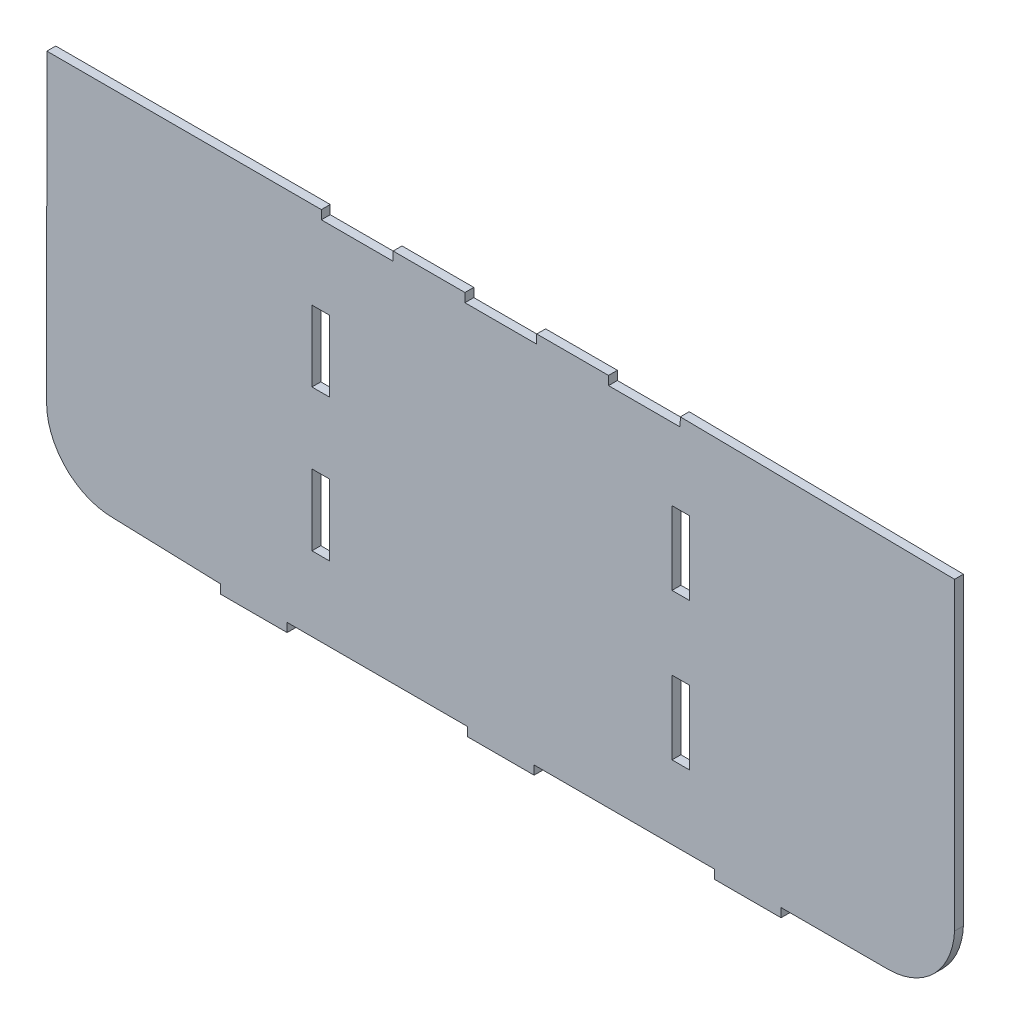
SolidWorks part; units mm, degrees
ref_plane "Front Plane" through (0, 0, 0) normal (0, 0, 1) x (1, 0, 0)
ref_plane "Top Plane" through (0, 0, 0) normal (0, 1, 0) x (1, 0, 0)
ref_plane "Right Plane" through (0, 0, 0) normal (1, 0, 0) x (0, 0, -1)
sketch "Sketch1" plane through (0, 0, 0) normal (0, 0, 1) x (1, 0, 0)
  line L12 (-444.5, 10.16) -> (-321.2, 6.2241)
  line L16 (-245, 6.2241) -> (-38.1, 6.2241)
  line L20 (38.1, 6.2241) -> (245, 6.2241)
  line L27 (205.7064, 435.61) -> (205.558, 425.45)
  line L28 (205.558, 425.45) -> (123.444, 425.45)
  line L29 (123.444, 425.45) -> (123.444, 435.61)
  line L30 (123.444, 435.61) -> (41.148, 435.61)
  line L31 (41.148, 435.61) -> (41.148, 425.45)
  line L32 (41.148, 425.45) -> (-41.148, 425.45)
  line L33 (-41.148, 425.45) -> (-41.148, 435.61)
  line L34 (-41.148, 435.61) -> (-123.444, 435.61)
  line L35 (-123.444, 435.61) -> (-123.444, 425.45)
  line L36 (-123.444, 425.45) -> (-205.74, 425.45)
  line L37 (-205.74, 425.45) -> (-205.74, 388.35)
  line L38 (-205.74, 388.35) -> (-230.3597, 388.35)
  line L39 (-520.3601, 435.61) -> (-520.7, 86.36)
  line L43 (-38.1, 6.2241) -> (-38.1, -3.9359) construction
  line L45 (38.1, 6.2241) -> (38.1, -3.9359) construction
  line L46 (38.1, 6.2241) -> (38.1, -3.9359)
  line L47 (-38.1, 6.2241) -> (-38.1, -3.9359)
  line L48 (245, 6.2241) -> (245, -3.9359) construction
  line L49 (321.2, 6.2241) -> (321.2, -3.9359) construction
  line L50 (245, 6.2241) -> (245, -3.9359)
  line L51 (321.2, 6.2241) -> (321.2, -3.9359)
  line L52 (-245, 6.2241) -> (-245, -3.9359) construction
  line L53 (-321.2, 6.2241) -> (-321.2, -3.9359) construction
  line L54 (-321.2, 6.2241) -> (-321.2, -3.9359)
  line L55 (-245, 6.2241) -> (-245, -3.9359)
  line L56 (216.5353, 174.4512) -> (216.5353, 90.3376) construction
  line L57 (216.5353, 342.6783) -> (216.5353, 258.5647) construction
  line L58 (216.5353, 174.4512) -> (216.5353, 90.3376)
  line L59 (216.5353, 342.6783) -> (216.5353, 258.5647)
  line L60 (-205.74, 425.45) -> (-205.74, 435.61)
  line L61 (-205.74, 435.61) -> (-520.3601, 435.61)
  line L62 (-216.5353, 172.7939) -> (-216.5353, 91.4769)
  line L63 (-216.5353, 335.4278) -> (-216.5353, 254.1108)
  line L64 (196.2153, 342.6783) -> (196.2153, 258.5647)
  line L65 (-196.2153, 335.4278) -> (-196.2153, 254.1108)
  line L66 (-196.2153, 172.7939) -> (-196.2153, 91.4769)
  line L67 (196.2153, 174.4512) -> (196.2153, 90.3376)
  line L68 (196.2153, 342.6783) -> (216.5353, 342.6783)
  line L69 (-196.2153, 335.4278) -> (-216.5353, 335.4278)
  line L70 (-216.5353, 254.1108) -> (-196.2153, 254.1108)
  line L71 (-196.2153, 172.7939) -> (-216.5353, 172.7939)
  line L72 (-196.2153, 91.4769) -> (-216.5353, 91.4769)
  line L73 (196.2153, 90.3376) -> (216.5353, 90.3376)
  line L74 (216.5353, 174.4512) -> (196.2153, 174.4512)
  line L75 (216.5353, 258.5647) -> (196.2153, 258.5647)
  line L76 (-520.3601, 435.61) -> (-520.3601, 465.8105)
  line L77 (-520.3601, 465.8105) -> (-530.3597, 465.719)
  line L78 (-530.3597, 465.719) -> (-530.3597, 494.219)
  line L79 (-530.3597, 494.219) -> (-230.3597, 494.219)
  line L81 (321.2, -3.9359) -> (245, -3.9359)
  line L82 (38.1, -3.9359) -> (-38.1, -3.9359)
  line L83 (-245, -3.9359) -> (-321.2, -3.9359)
  line L84 (-230.3597, 494.219) -> (-230.3597, 388.35)
  line L85 (520.0465, 82.2641) -> (520.0703, 431.5141) construction
  line L86 (520.0465, 82.2641) -> (520.0703, 431.5141)
  line L87 (444.5, 6.2241) -> (321.2, 6.2241)
  line L88 (-520.3601, 435.61) -> (580.4446, 435.61) construction
  line L89 (-123.444, 425.45) -> (629.1878, 425.45) construction
  line L90 (205.7064, 435.61) -> (520.0703, 431.5141)
  line L91 (-205.74, 435.61) -> (-230.3597, 435.61)
  line L92 (-230.3597, 435.61) -> (-230.3597, 388.35)
  line L94 (-230.3597, 388.35) -> (-205.74, 388.35)
  line L95 (-230.3597, 388.35) -> (-230.3597, 435.61)
  line L96 (-230.3597, 435.61) -> (-205.74, 435.61)
  line L97 (-205.74, 388.35) -> (-205.74, 435.61)
  arc A0 (-520.7, 86.36) -> (-444.5, 10.16) centre (-444.5, 86.36) ccw
  ellipse E3 centre (443.8465, 86.3572) end of major axis (443.8465, 166.4932) minor radius 76.2996 (444.5, 6.2241) -> (520.0465, 82.2641) ccw
  dimension "D2" = 20.32
  dimension "D1" = 28.5
  dimension "D4" = 20.32
  dimension "D5" = 20.32
  dimension "D6" = 20.32
  dimension "D7" = 300
other "AlignGroup1"
extrude "Boss-Extrude1" add sketch "Sketch1" along normal blind 10.16 contours L87 E3 L86 L90 L27 L28 L29 L30 L31 L32 L33 L34 L35 L36 L37 L38 L84 L61 L39 A0 L12 L54 L83 L55 L16 L47 L82 L46 L20 L50 L81 L51 L59 L75 L64 L68 L66 L72 L62 L71 L70 L63 L69 L65 L74 L58 L73 | L61 L84 L38 L37 L60
